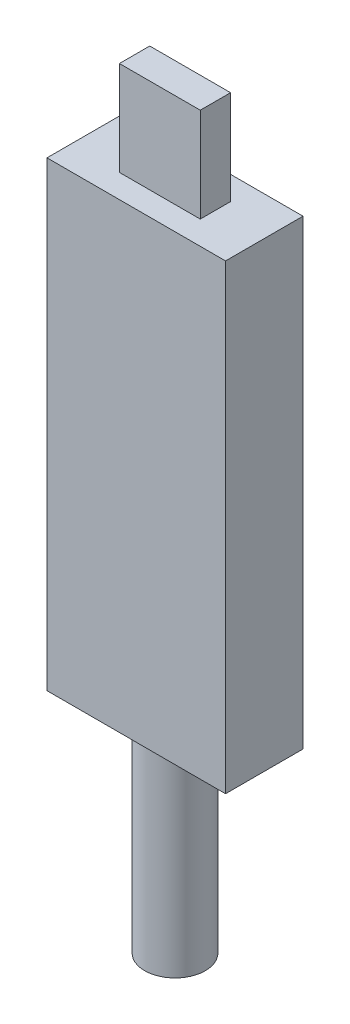
SolidWorks part; units mm, degrees
ref_plane "前视基准面" through (0, 0, 0) normal (0, 0, 1) x (1, 0, 0)
ref_plane "上视基准面" through (0, 0, 0) normal (0, 1, 0) x (1, 0, 0)
ref_plane "右视基准面" through (0, 0, 0) normal (1, 0, 0) x (0, 0, -1)
other "Configuration Table"
sketch "草图1" plane through (0, 0, 0) normal (0, 1, 0) x (1, 0, 0)
  line L1 (-12.4103, 3.7564) -> (14.0897, 3.7564)
  line L2 (-12.4103, 3.7564) -> (-12.4103, -7.7436)
  line L3 (-12.4103, -7.7436) -> (14.0897, -7.7436)
  line L4 (14.0897, 3.7564) -> (14.0897, -7.7436)
  dimension "D1" = 26.5
  dimension "D2" = 11.5
extrude "凸台-拉伸1" add sketch "草图1" along normal blind 68.5
sketch "草图2" plane through (0, 68.5, 0) normal (0, 1, 0) x (1, 0, 0)
  line L0 (14.0897, 3.7564) -> (-12.4103, 3.7564) construction
  line L1 (-5.1603, 0.2564) -> (6.8397, 0.2564)
  line L2 (-5.1603, 0.2564) -> (-5.1603, -4.2436)
  line L3 (-5.1603, -4.2436) -> (6.8397, -4.2436)
  line L4 (6.8397, 0.2564) -> (6.8397, -4.2436)
  line L5 (-12.4103, 3.7564) -> (-12.4103, -7.7436) construction
  point P6 (0.8397, 3.7564)
  point P7 (0.8397, 0.2564)
  point P10 (-12.4103, -1.9936)
  point P11 (-5.1603, -1.9936)
  dimension "D1" = 12
  dimension "D2" = 4.5
extrude "凸台-拉伸2" add sketch "草图2" along normal blind 14
sketch "草图3" plane through (0, 0, 0) normal (0, -1, 0) x (1, 0, 0)
  line L0 (-12.4103, 7.7436) -> (14.0897, 7.7436) construction
  line L1 (-12.4103, -3.7564) -> (-12.4103, 7.7436) construction
  circle A0 centre (0.8397, 1.9936) radius 4.5
  point P4 (0.8397, 7.7436)
  point P7 (-12.4103, 1.9936)
  dimension "D1" = 9
extrude "凸台-拉伸3" add sketch "草图3" along normal blind 30
